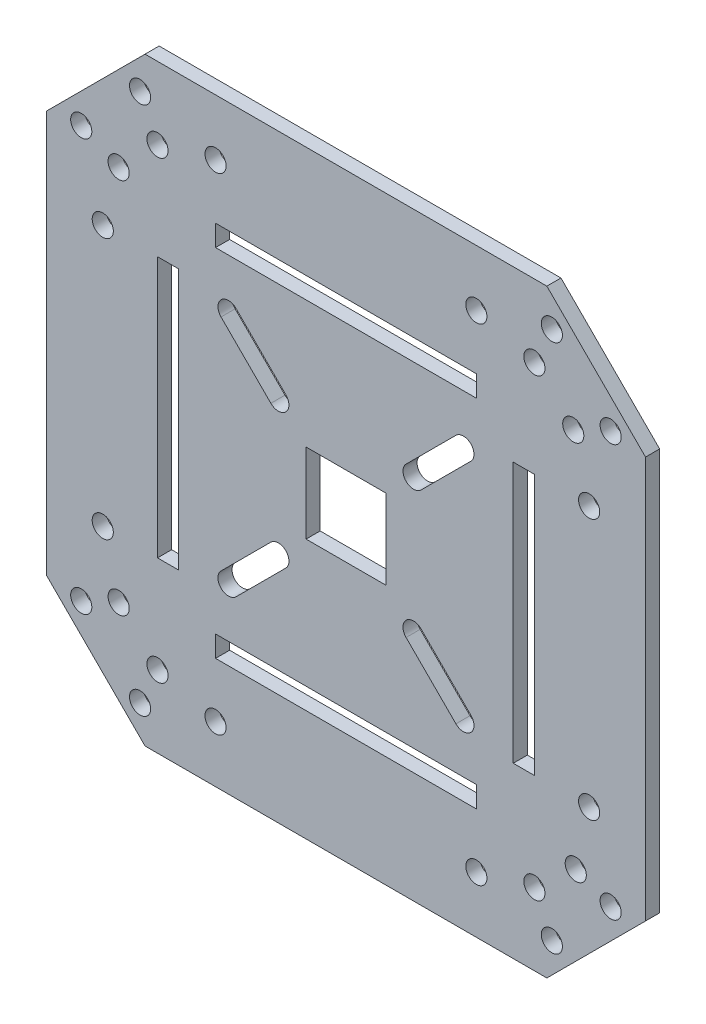
SolidWorks part; units mm, degrees
ref_plane "前视基准面" through (0, 0, 0) normal (0, 0, 1) x (1, 0, 0)
ref_plane "上视基准面" through (0, 0, 0) normal (0, 1, 0) x (1, 0, 0)
ref_plane "右视基准面" through (0, 0, 0) normal (1, 0, 0) x (0, 0, -1)
other "Configuration Table"
sketch "草图1" plane through (0, 0, 0) normal (0, 0, 1) x (1, 0, 0)
  line L2 (0, 0) -> (85, 0)
  line L3 (0, 0) -> (0, 85)
  line L4 (0, 85) -> (85, 85)
  line L5 (85, 0) -> (85, 85)
extrude "凸台-拉伸1" add sketch "草图1" along normal blind 2 contours L4 L5 L2 L3
sketch "草图2" plane through (0, 0, 0) normal (0, 0, 1) x (1, 0, 0)
  line L0 (0, 85) -> (14, 85)
  line L1 (0, 85) -> (85, 85) construction
  line L2 (0, 85) -> (0, 71)
  line L3 (0, 0) -> (0, 85) construction
  line L4 (14, 85) -> (0, 71)
  line L8 (0, 0) -> (14, 0)
  line L9 (0, 0) -> (85, 0) construction
  line L10 (0, 0) -> (0, 14)
  line L11 (0, 14) -> (14, 0)
  line L12 (85, 85) -> (71, 85)
  line L13 (85, 85) -> (85, 71)
  line L14 (85, 0) -> (85, 85) construction
  line L15 (71, 85) -> (85, 71)
  line L16 (85, 0) -> (85, 14)
  line L17 (85, 0) -> (71, 0)
  line L18 (85, 14) -> (71, 0)
extrude "切除-拉伸1" cut sketch "草图2" along normal blind 3
sketch "草图4" plane through (0, 0, 0) normal (0, 0, 1) x (1, 0, 0)
  circle A0 centre (13.2929, 80.0503) radius 1.5
  circle A1 centre (4.9497, 71.7071) radius 1.5
  circle A4 centre (10.253, 69.2322) radius 1.5
  circle A5 centre (15.7678, 74.747) radius 1.5
  circle A6 centre (4.9497, 13.2929) radius 1.5
  circle A7 centre (13.2929, 4.9497) radius 1.5
  circle A8 centre (10.253, 15.7678) radius 1.5
  circle A9 centre (15.7678, 10.253) radius 1.5
  circle A10 centre (71.7071, 4.9497) radius 1.5
  circle A11 centre (69.2322, 10.253) radius 1.5
  circle A12 centre (75.1005, 15.4142) radius 1.5
  circle A13 centre (80.0503, 13.2929) radius 1.5
  circle A14 centre (71.7071, 80.0503) radius 1.5
  circle A15 centre (69.2322, 74.747) radius 1.5
  circle A16 centre (74.747, 69.2322) radius 1.5
  circle A17 centre (80.0503, 71.7071) radius 1.5
extrude "切除-拉伸2" cut sketch "草图4" along normal blind 3
sketch "草图5" plane through (0, 0, 0) normal (0, 0, 1) x (1, 0, 0)
  circle A0 centre (8, 61) radius 1.5
  circle A1 centre (8, 24) radius 1.5
  circle A2 centre (24, 8) radius 1.5
  circle A3 centre (61, 8) radius 1.5
  circle A4 centre (77, 24) radius 1.5
  circle A5 centre (77, 61) radius 1.5
  circle A6 centre (61, 77) radius 1.5
  circle A7 centre (24, 77) radius 1.5
extrude "切除-拉伸3" cut sketch "草图5" along normal blind 2
sketch "草图6" plane through (0, 0, 0) normal (0, 0, 1) x (1, 0, 0)
  line L2 (24, 15.7678) -> (61, 15.7678)
  line L6 (24, 69.2322) -> (61, 69.2322)
  line L7 (24, 69.2322) -> (24, 66.2322)
  line L8 (24, 66.2322) -> (61, 66.2322)
  line L9 (61, 69.2322) -> (61, 66.2322)
  line L12 (15.7678, 61) -> (18.7678, 61)
  line L13 (15.7678, 61) -> (15.7678, 24)
  line L14 (15.7678, 24) -> (18.7678, 24)
  line L15 (18.7678, 61) -> (18.7678, 24)
  line L17 (24, 15.7678) -> (24, 18.7678)
  line L18 (24, 18.7678) -> (61, 18.7678)
  line L19 (61, 15.7678) -> (61, 18.7678)
  line L20 (69.2322, 61) -> (66.2322, 61)
  line L21 (69.2322, 61) -> (69.2322, 24)
  line L22 (69.2322, 24) -> (66.2322, 24)
  line L23 (66.2322, 61) -> (66.2322, 24)
  line L28 (25.8388, 59.1612) -> (32.9099, 52.0901) construction
  line L29 (26.8995, 60.2218) -> (33.9706, 53.1508)
  line L30 (24.7782, 58.1005) -> (31.8492, 51.0294)
  line L32 (25.8388, 25.8388) -> (32.9099, 32.9099) construction
  line L33 (24.7782, 26.8995) -> (31.8492, 33.9706)
  line L34 (26.8995, 24.7782) -> (33.9706, 31.8492)
  line L36 (59.1612, 59.1612) -> (52.0901, 52.0901) construction
  line L37 (60.2218, 58.1005) -> (53.1508, 51.0294)
  line L38 (58.1005, 60.2218) -> (51.0294, 53.1508)
  line L40 (59.1612, 25.8388) -> (52.0901, 32.9099) construction
  line L41 (58.1005, 24.7782) -> (51.0294, 31.8492)
  line L42 (60.2218, 26.8995) -> (53.1508, 33.9706)
  line L44 (36.8431, 48.1569) -> (36.8431, 36.8431)
  line L45 (36.8431, 36.8431) -> (48.1569, 36.8431)
  line L46 (48.1569, 36.8431) -> (48.1569, 48.1569)
  line L47 (48.1569, 48.1569) -> (36.8431, 48.1569)
  arc A0 (26.8995, 60.2218) -> (24.7782, 58.1005) centre (25.8388, 59.1612) ccw
  arc A1 (31.8492, 51.0294) -> (33.9706, 53.1508) centre (32.9099, 52.0901) ccw
  arc A2 (24.7782, 26.8995) -> (26.8995, 24.7782) centre (25.8388, 25.8388) ccw
  arc A3 (33.9706, 31.8492) -> (31.8492, 33.9706) centre (32.9099, 32.9099) ccw
  arc A4 (60.2218, 58.1005) -> (58.1005, 60.2218) centre (59.1612, 59.1612) ccw
  arc A5 (51.0294, 53.1508) -> (53.1508, 51.0294) centre (52.0901, 52.0901) ccw
  arc A6 (58.1005, 24.7782) -> (60.2218, 26.8995) centre (59.1612, 25.8388) ccw
  arc A7 (53.1508, 33.9706) -> (51.0294, 31.8492) centre (52.0901, 32.9099) ccw
  point P0 (29.3744, 55.6256)
  point P19 (29.3744, 29.3744)
  point P34 (55.6256, 55.6256)
  point P41 (55.6256, 29.3744)
extrude "切除-拉伸4" cut sketch "草图6" along normal blind 2
